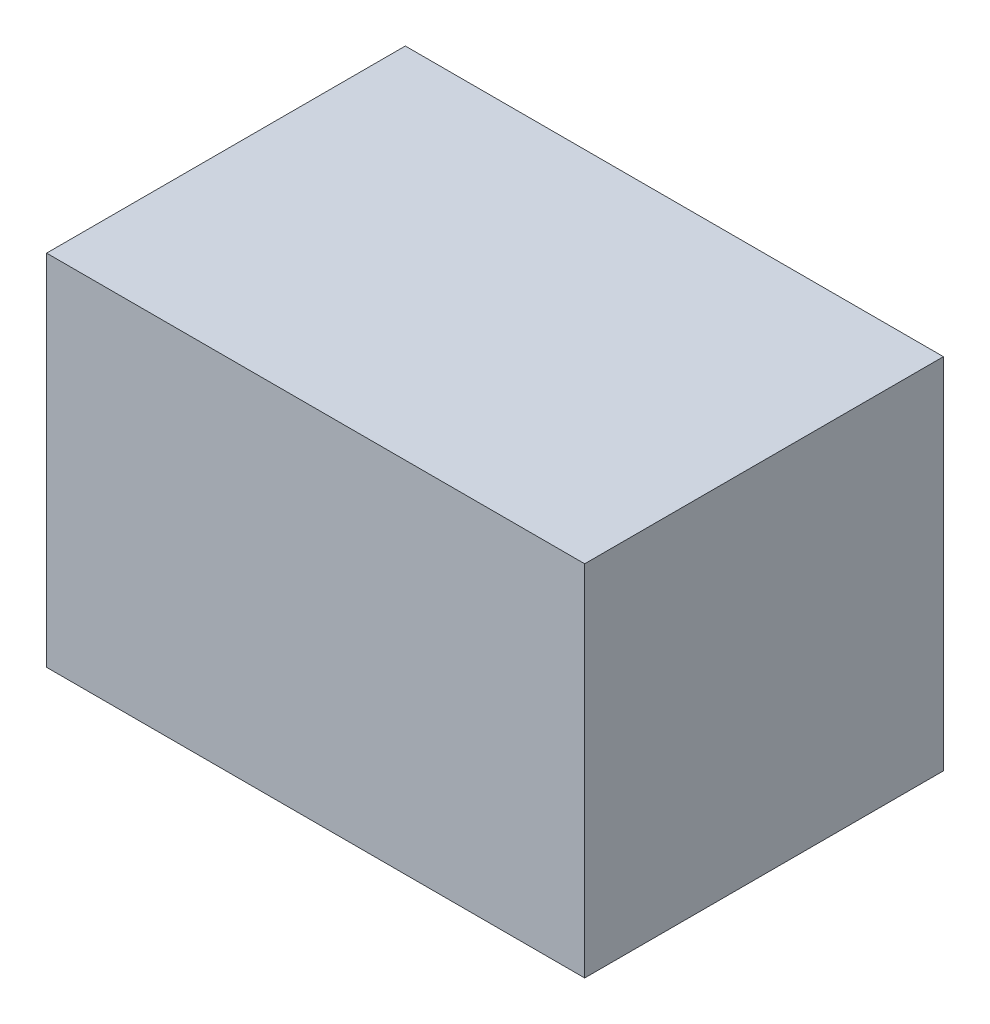
SolidWorks part; units mm, degrees
ref_plane "Front Plane" through (0, 0, 0) normal (0, 0, 1) x (1, 0, 0)
ref_plane "Top Plane" through (0, 0, 0) normal (0, 1, 0) x (1, 0, 0)
ref_plane "Right Plane" through (0, 0, 0) normal (1, 0, 0) x (0, 0, -1)
sketch "Sketch1" plane through (0, 0, 0) normal (0, 1, 0) x (1, 0, 0)
  line L1 (-855.4065, 781.6645) -> (1887.7935, 781.6645)
  line L2 (-855.4065, 781.6645) -> (-855.4065, -1047.1355)
  line L3 (-855.4065, -1047.1355) -> (1887.7935, -1047.1355)
  line L4 (1887.7935, 781.6645) -> (1887.7935, -1047.1355)
  dimension "D1" = 1828.8
  dimension "D2" = 2743.2
extrude "Boss-Extrude1" add sketch "Sketch1" along normal blind 1828.8
